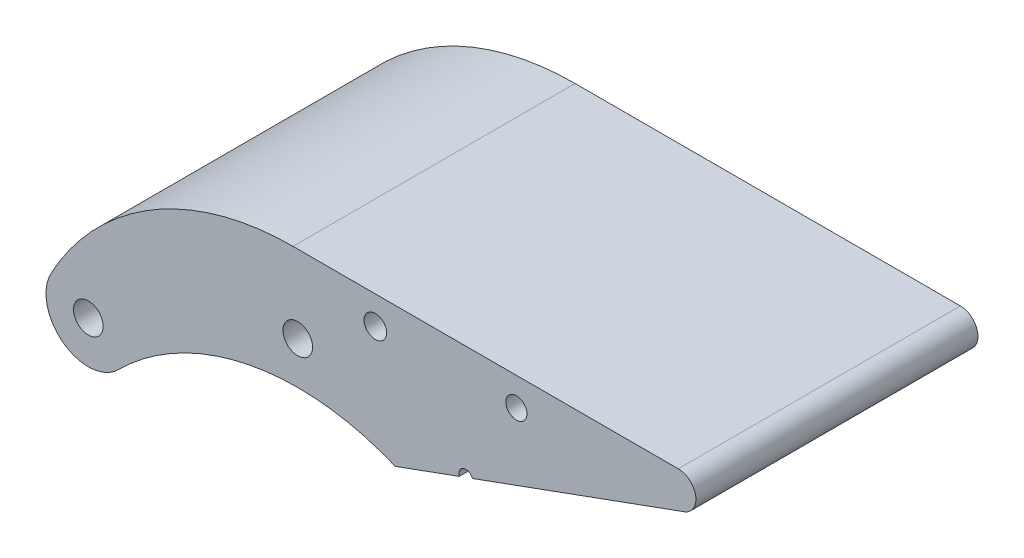
SolidWorks part; units mm, degrees
material "ABS"
ref_plane "前视基准面" through (0, 0, 0) normal (0, 0, 1) x (1, 0, 0)
ref_plane "上视基准面" through (0, 0, 0) normal (0, 1, 0) x (1, 0, 0)
ref_plane "右视基准面" through (0, 0, 0) normal (1, 0, 0) x (0, 0, -1)
other "Configuration Table"
sketch "草图1" plane through (0, 0, 0) normal (0, 0, 1) x (1, 0, 0)
  line L0 (0, 42) -> (0, 0) construction
  line L1 (0, 0) -> (-29.6985, 29.6985) construction
  line L2 (-29.6985, 53) -> (68.1355, 53)
  line L3 (-9.0635, 24.9019) -> (68.1355, 53)
  line L4 (0, 0) -> (13.8339, 33.2359) construction
  line L5 (0, 0) -> (-9.0635, 24.9019) construction
  circle A0 centre (0, 0) radius 42 construction
  circle A1 centre (0, 42) radius 2.1
  circle A2 centre (-29.6985, 29.6985) radius 2.1
  circle A3 centre (-29.6985, 29.6985) radius 6
  circle A4 centre (0, 0) radius 36
  circle A7 centre (-0.6716, 14) radius 39
  circle A8 centre (0, 0) radius 26.5 construction
  dimension "D1" = 84
  dimension "D2" = 4.2
  dimension "D3" = 45
  dimension "D4" = 72
  dimension "D6" = 78
  dimension "D9" = 53
  dimension "D5" = 53
  dimension "D7" = 20
extrude "凸台-拉伸1" add sketch "草图1" along normal blind 40
fillet "圆角1" radius 2.5 1 edges at (68.1355, 53, 20)
sketch "草图3" plane through (0, 0, 40) normal (0, 0, 1) x (1, 0, 0)
  line L0 (-0.6716, 53) -> (53.9573, 53) construction
  circle A0 centre (11, 49) radius 1.6
  circle A1 centre (31, 49) radius 1.5
  circle A3 centre (0, 42) radius 2.1 construction
  circle A4 centre (0, 42) radius 2.1
  dimension "D2" = 3.2
  dimension "D3" = 3
  dimension "D5" = 11
  dimension "D1" = 20
  dimension "D4" = 4
extrude "切除-拉伸2" cut sketch "草图3" against normal up to next (40 mm away)
sketch "草图4" plane through (0, 0, 40) normal (0, 0, 1) x (1, 0, 0)
  line L0 (13.8339, 33.2359) -> (54.8123, 48.1508) construction
  line L1 (13.8339, 33.2359) -> (54.8123, 48.1508)
  circle A0 centre (23.8339, 36.8756) radius 1
  dimension "D1" = 2
  dimension "D2" = 10
extrude "切除-拉伸3" cut sketch "草图4" against normal up to next contours A0
